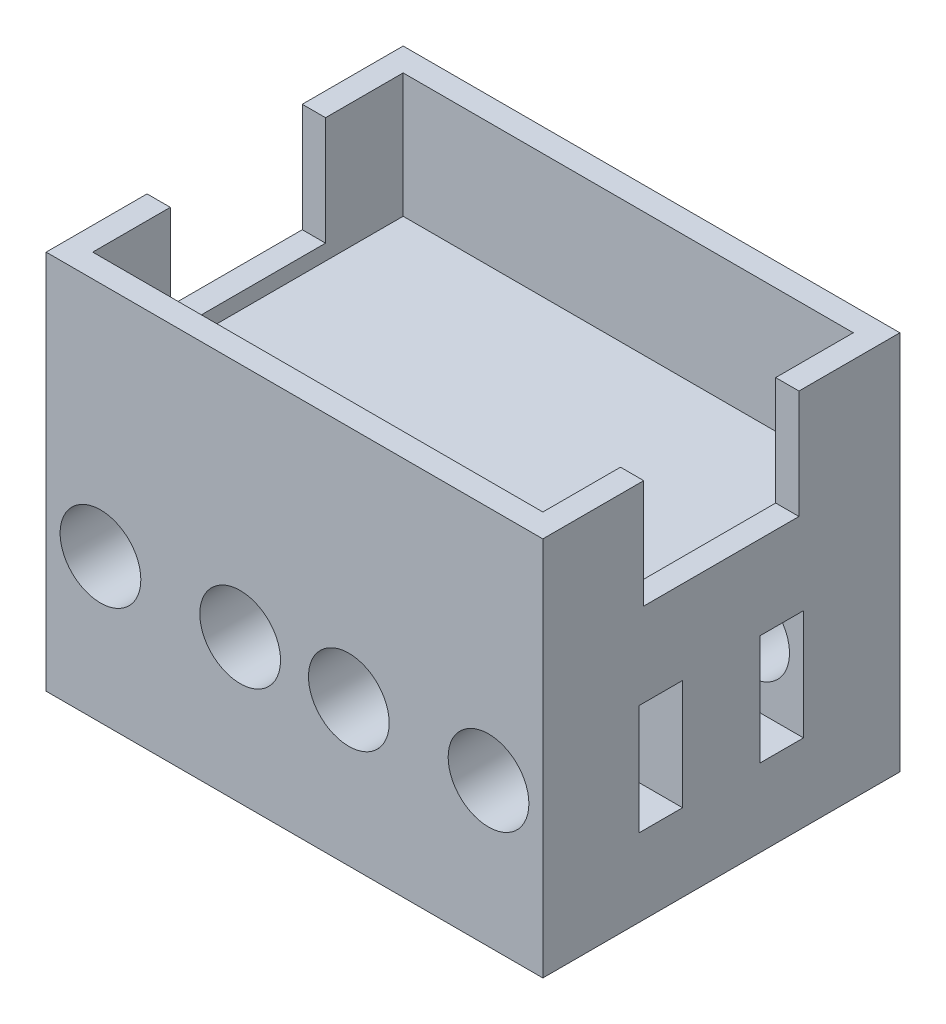
SolidWorks part; units mm, degrees
ref_plane "Front Plane" through (0, 0, 0) normal (0, 0, 1) x (1, 0, 0)
ref_plane "Top Plane" through (0, 0, 0) normal (0, 1, 0) x (1, 0, 0)
ref_plane "Right Plane" through (0, 0, 0) normal (1, 0, 0) x (0, 0, -1)
sketch "Sketch4" plane through (0, 0, 0) normal (0, 1, 0) x (1, 0, 0)
  line L1 (-16, -11.5) -> (16, -11.5)
  line L2 (-16, -11.5) -> (-16, 11.5)
  line L3 (-16, 11.5) -> (16, 11.5)
  line L4 (16, -11.5) -> (16, 11.5)
  line L5 (-16, -11.5) -> (16, 11.5) construction
  line L6 (-16, 11.5) -> (16, -11.5) construction
  point P0 (0, 0)
  dimension "D1" = 32
  dimension "D2" = 23
extrude "Boss-Extrude3" add sketch "Sketch4" along normal blind 9.5
sketch "Sketch5" plane through (0, 9.5, 0) normal (0, 1, 0) x (1, 0, 0)
  line L1 (-14.5, -10) -> (14.5, -10)
  line L2 (-14.5, -10) -> (-14.5, 10)
  line L3 (-14.5, 10) -> (14.5, 10)
  line L4 (14.5, -10) -> (14.5, 10)
  line L5 (-14.5, -10) -> (14.5, 10) construction
  line L6 (-14.5, 10) -> (14.5, -10) construction
  point P0 (0, 0)
  dimension "D1" = 29
  dimension "D2" = 20
extrude "Cut-Extrude2" cut sketch "Sketch5" against normal blind 8
sketch "Sketch7" plane through (16, 0, 0) normal (1, 0, 0) x (0, 0, -1)
  line L1 (-5, 2.5) -> (5, 2.5)
  line L2 (-5, 2.5) -> (-5, 9.5)
  line L3 (-5, 9.5) -> (5, 9.5)
  line L4 (5, 2.5) -> (5, 9.5)
  line L5 (-11.5, 9.5) -> (11.5, 9.5) construction
  point P6 (0, 9.5)
  point P8 (0, 9.5)
  dimension "D1" = 10
  dimension "D2" = 7
extrude "Cut-Extrude4" cut sketch "Sketch7" against normal through all
sketch "Sketch8" plane through (0, 0, 0) normal (0, -1, 0) x (-1, 0, 0)
  line L17 (-16, -11.5) -> (16, -11.5)
  line L18 (-16, -11.5) -> (-16, 11.5)
  line L19 (-16, 11.5) -> (16, 11.5)
  line L20 (16, -11.5) -> (16, 11.5)
  line L21 (-16, -11.5) -> (16, 11.5) construction
  line L22 (-16, 11.5) -> (16, -11.5) construction
  point P4 (0, 0)
extrude "Boss-Extrude4" add sketch "Sketch8" along normal blind 10
ref_plane "Plane1" through (0, 0, 0) normal (0, 0, -1) x (-1, 0, 0)
sketch "Sketch12" plane through (0, 0, -11.5) normal (0, 0, -1) x (-1, 0, 0)
  line L0 (0, 9.5) -> (0, -10) construction
  line L1 (-16, 9.5) -> (16, 9.5) construction
  line L2 (16, -10) -> (-16, -10) construction
  line L3 (-16, 9.5) -> (0, -10) construction
  line L4 (0, 9.5) -> (-16, -10) construction
  line L5 (-8, -0.25) -> (-8, -10) construction
  line L6 (-16, 9.5) -> (-16, -10) construction
  circle A0 centre (-12.5, -5.7269) radius 2.6
  circle A1 centre (-3.5, -5.7269) radius 2.6
  circle A2 centre (3.5, -5.7269) radius 2.6
  circle A3 centre (12.5, -5.7269) radius 2.6
  dimension "D1" = 5.2
  dimension "D3" = 3.5
  dimension "D2" = 4.2731
extrude "Cut-Extrude5" cut sketch "Sketch12" against normal blind 7
pattern_circular "CirPattern1" count 2 over 180 about axis through (0, 1.5, 0) along (0, -1, 0) of "Cut-Extrude5"
sketch "Sketch13" plane through (0, -10, 0) normal (0, -1, 0) x (-1, 0, 0)
  line L0 (16, -11.5) -> (16, 11.5) construction
  line L1 (16, 2.5) -> (1, 2.5)
  line L2 (16, 2.5) -> (16, 5.2916)
  line L3 (16, 5.2916) -> (1, 5.2916)
  line L4 (1, 2.5) -> (1, 5.2916)
  line L5 (16, 2.5) -> (1, 5.2916) construction
  line L6 (16, 5.2916) -> (1, 2.5) construction
  line L7 (10.725, 0) -> (-10.725, 0) construction
  line L8 (0, -11.5) -> (0, 11.5) construction
  line L9 (-16, -11.5) -> (16, -11.5) construction
  line L10 (16, 11.5) -> (-16, 11.5) construction
  line L11 (-16, 5.2916) -> (-1, 5.2916)
  line L12 (-1, 2.5) -> (-1, 5.2916)
  line L13 (-16, 2.5) -> (-1, 2.5)
  line L14 (-16, 2.5) -> (-16, 5.2916)
  line L15 (-16, -2.5) -> (-16, -5.2916)
  line L16 (-16, -2.5) -> (-1, -2.5)
  line L17 (-1, -2.5) -> (-1, -5.2916)
  line L18 (-16, -5.2916) -> (-1, -5.2916)
  line L19 (16, -5.2916) -> (1, -5.2916)
  line L20 (1, -2.5) -> (1, -5.2916)
  line L21 (16, -2.5) -> (1, -2.5)
  line L22 (16, -2.5) -> (16, -5.2916)
  point P4 (8.5, 3.8958)
  dimension "D1" = 15
  dimension "D2" = 2.7916
  dimension "D3" = 2.5
extrude "Cut-Extrude6" cut sketch "Sketch13" against normal blind 7.1
sketch "Sketch14" plane through (0, -10, 0) normal (0, -1, 0) x (-1, 0, 0)
  line L1 (16, 11.5) -> (-16, 11.5)
  line L2 (16, 11.5) -> (16, -11.5)
  line L3 (16, -11.5) -> (-16, -11.5)
  line L4 (-16, 11.5) -> (-16, -11.5)
  line L5 (16, 11.5) -> (-16, -11.5) construction
  line L6 (16, -11.5) -> (-16, 11.5) construction
  point P4 (0, 0)
extrude "Boss-Extrude5" add sketch "Sketch14" along normal blind 5
